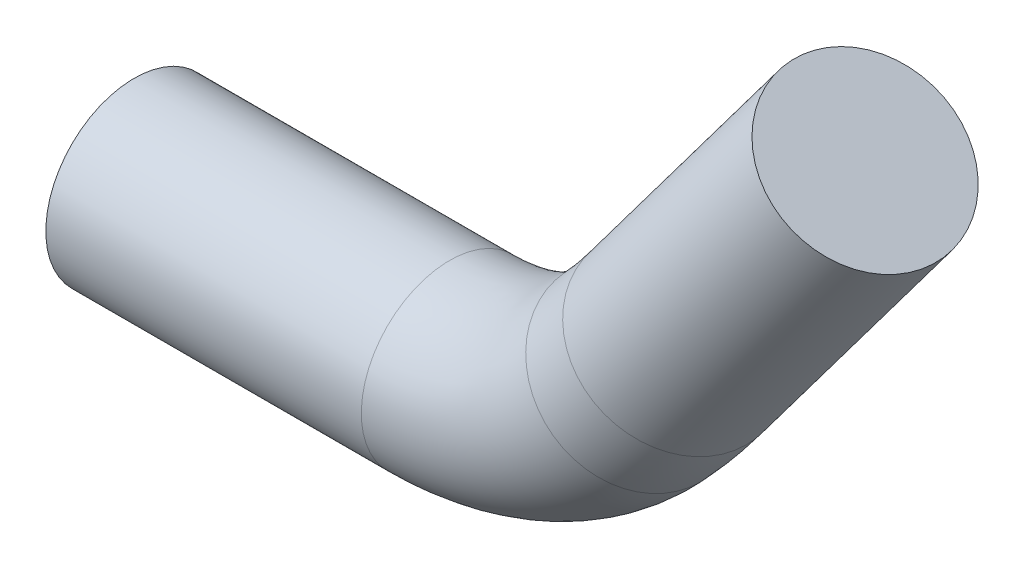
SolidWorks part; units mm, degrees
ref_plane "Front Plane" through (0, 0, 0) normal (0, 0, 1) x (1, 0, 0)
ref_plane "Top Plane" through (0, 0, 0) normal (0, 1, 0) x (1, 0, 0)
ref_plane "Right Plane" through (0, 0, 0) normal (1, 0, 0) x (0, 0, -1)
sketch "Sketch1" plane through (0, 0, 0) normal (1, 0, 0) x (0, 0, -1)
  circle A0 centre (0, 0) radius 3.556
  dimension "D1" = 7.112
sketch "Sketch3" plane through (0, 0, 0) normal (0, 0, 1) x (1, 0, 0)
  line L0 (0, 0) -> (12.7, 0)
  line L1 (21.8033, 5.2371) -> (29.4233, 15.3971)
  arc A0 (12.7, 0) -> (20.1778, 3.2819) centre (12.7, 10.16) ccw
  arc A1 (20.1778, 3.2819) -> (21.8033, 5.2371) centre (1.4833, 20.4771) ccw
  point P7 (35.006, 27.0871)
  point P12 (35.006, 21.9752)
  point P13 (0, 0)
  point P14 (0, 0)
  dimension "D2" = 10.16
  dimension "D3" = 25.4
  dimension "D1" = 12.7
  dimension "D4" = 10.16
  dimension "D5" = 15.24
  dimension "D8" = 12.7
sweep "Sweep1" add profiles "Sketch1" path "Sketch3"
